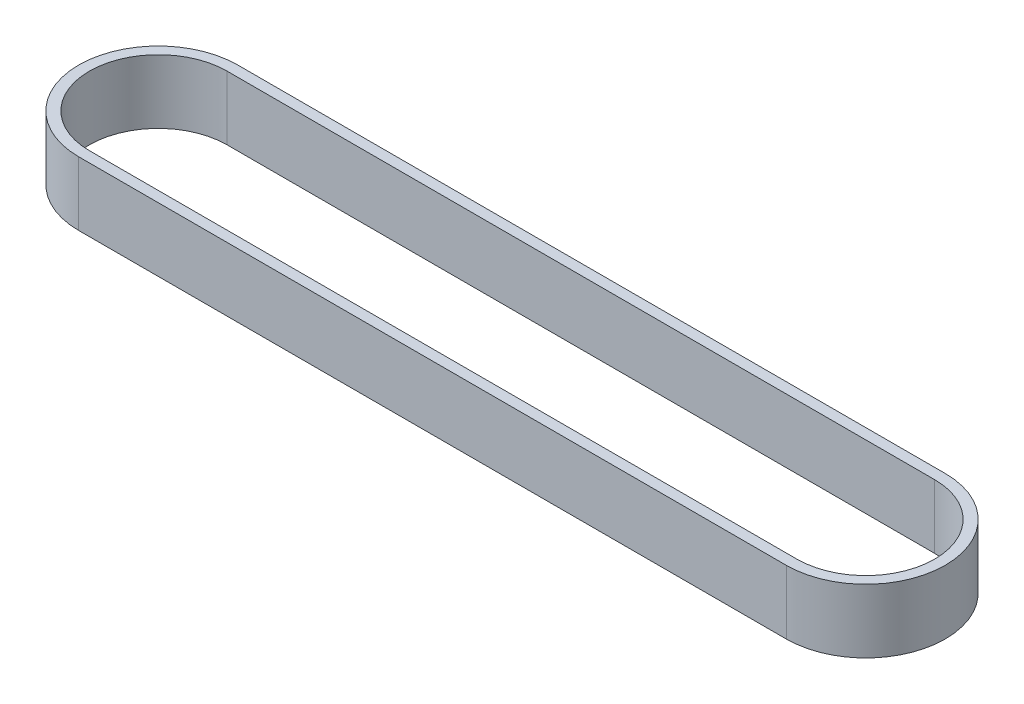
SolidWorks part; units mm, degrees
ref_plane "前视" through (0, 0, 0) normal (0, 0, 1) x (1, 0, 0)
ref_plane "上视" through (0, 0, 0) normal (0, 1, 0) x (1, 0, 0)
ref_plane "右视" through (0, 0, 0) normal (1, 0, 0) x (0, 0, -1)
sketch "草图1" plane through (0, 0, 0) normal (0, 1, 0) x (1, 0, 0)
  line L0 (-33.24, 7.47) -> (33.24, 7.47)
  line L1 (-33.24, 6.47) -> (33.24, 6.47)
  line L2 (-33.24, 6.47) -> (-33.24, -6.47) construction
  line L3 (-33.24, -6.47) -> (33.24, -6.47)
  line L4 (33.24, 6.47) -> (33.24, -6.47) construction
  line L5 (-33.24, 6.47) -> (33.24, -6.47) construction
  line L6 (-33.24, -6.47) -> (33.24, 6.47) construction
  line L7 (-33.24, -7.47) -> (33.24, -7.47)
  arc A0 (33.24, -6.47) -> (33.24, 6.47) centre (33.24, 0) ccw
  arc A1 (-33.24, 6.47) -> (-33.24, -6.47) centre (-33.24, 0) ccw
  arc A2 (33.24, -7.47) -> (33.24, 7.47) centre (33.24, 0) ccw
  arc A3 (-33.24, 7.47) -> (-33.24, -7.47) centre (-33.24, 0) ccw
  point P0 (0, 0)
  dimension "D1" = 12.94
  dimension "D2" = 66.48
  dimension "D3" = 1
extrude "凸台-拉伸1" add sketch "草图1" along normal blind 6
